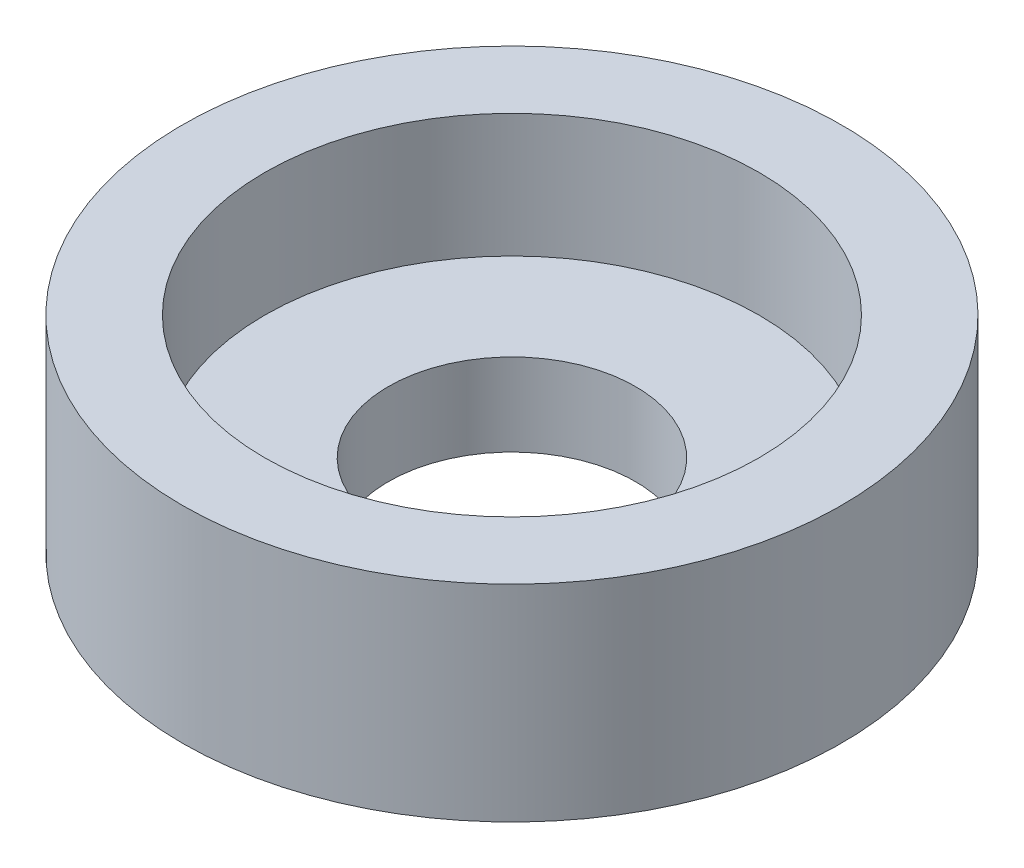
SolidWorks part; units mm, degrees
ref_plane "前视基准面" through (0, 0, 0) normal (0, 0, 1) x (1, 0, 0)
ref_plane "上视基准面" through (0, 0, 0) normal (0, 1, 0) x (1, 0, 0)
ref_plane "右视基准面" through (0, 0, 0) normal (1, 0, 0) x (0, 0, -1)
sketch "草图1" plane through (0, 0, 0) normal (0, 1, 0) x (1, 0, 0)
  circle A0 centre (0, 0) radius 8
  dimension "D1" = 16
extrude "凸台-拉伸1" add sketch "草图1" along normal blind 5
sketch "草图2" plane through (0, 5, 0) normal (0, 1, 0) x (1, 0, 0)
  circle A0 centre (0, 0) radius 6
  dimension "D1" = 12
extrude "切除-拉伸1" cut sketch "草图2" against normal offset from surface (3 mm away) 2 up to face at (0, 0, 8)
sketch "草图3" plane through (0, 2, 0) normal (0, 1, 0) x (1, 0, 0)
  circle A0 centre (0, 0) radius 3
  dimension "D1" = 6
extrude "切除-拉伸2" cut sketch "草图3" against normal through all
